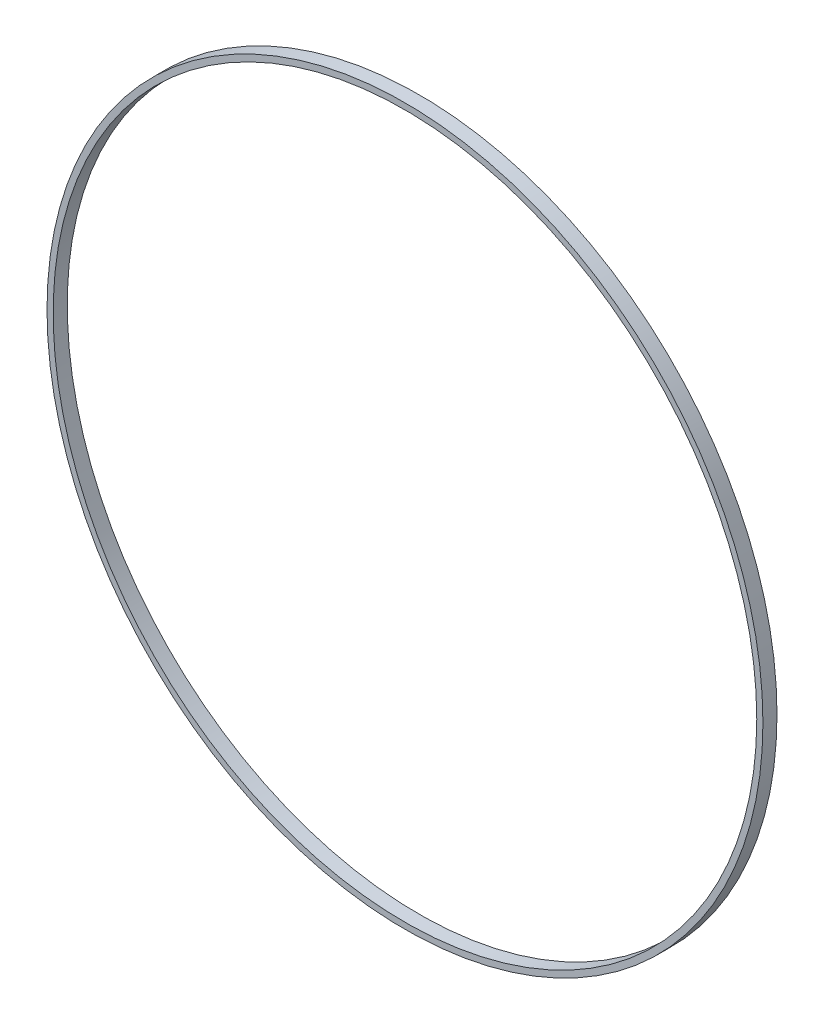
SolidWorks part; units mm, degrees
material "Caoutchouc"
ref_plane "Plan de face" through (0, 0, 0) normal (0, 0, 1) x (1, 0, 0)
ref_plane "Plan de dessus" through (0, 0, 0) normal (0, 1, 0) x (1, 0, 0)
ref_plane "Plan de droite" through (0, 0, 0) normal (1, 0, 0) x (0, 0, -1)
sketch "Esquisse1" plane through (0, 0, 0) normal (0, 0, 1) x (1, 0, 0)
  circle A0 centre (0, 0) radius 20
  circle A1 centre (0, 0) radius 20.35
  dimension "D1" = 40
  dimension "D2" = 0.35
extrude "Boss.-Extru.1" add sketch "Esquisse1" along normal blind 0.8
